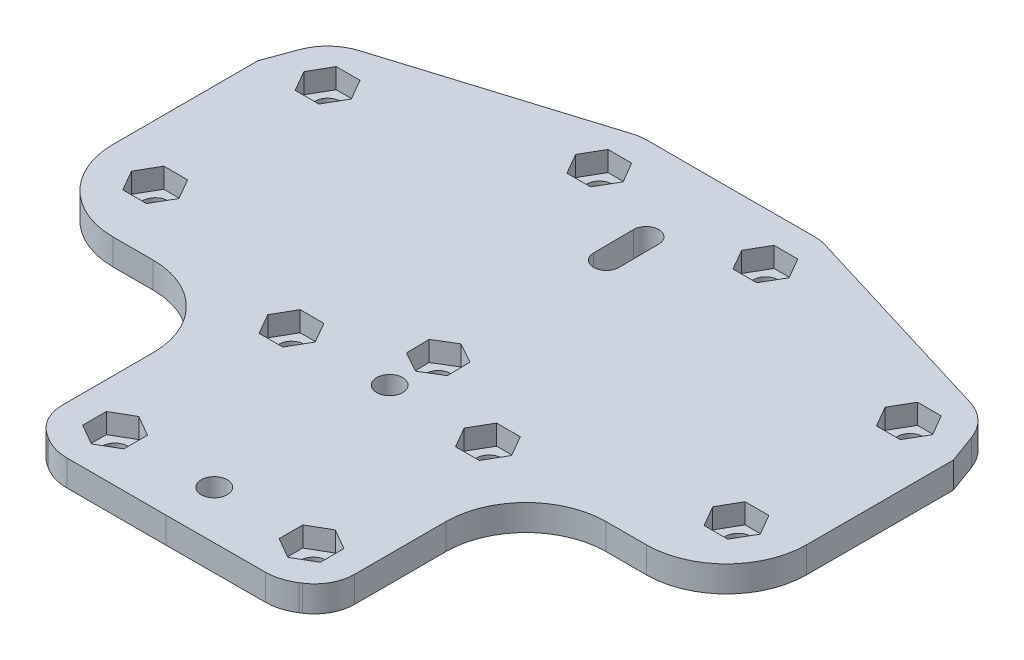
SolidWorks part; units mm, degrees
ref_plane "Front Plane" through (0, 0, 0) normal (0, 0, 1) x (1, 0, 0)
ref_plane "Top Plane" through (0, 0, 0) normal (0, 1, 0) x (1, 0, 0)
ref_plane "Right Plane" through (0, 0, 0) normal (1, 0, 0) x (0, 0, -1)
sketch "DimensionalReference" plane through (0, 0, 0) normal (0, 1, 0) x (1, 0, 0)
  line L0 (0, 0) -> (0, 54.3246) construction
  line L1 (-1000, 12.5) -> (1000, 12.5) construction
  line L2 (-1000, 12.5) -> (-1000, -12.5) construction
  line L3 (-1000, -12.5) -> (1000, -12.5) construction
  line L4 (1000, 12.5) -> (1000, -12.5) construction
  line L5 (-72.5, -22.5) -> (-72.5, 60.05) construction
  line L6 (0, 22.5) -> (0, -109.2175) construction
  line L7 (-12.5, -17.5) -> (12.9, -17.5) construction
  line L8 (-12.5, -17.5) -> (-12.5, -92.5) construction
  line L9 (-12.5, -92.5) -> (12.9, -92.5) construction
  line L10 (12.9, -17.5) -> (12.9, -92.5) construction
  line L11 (-104.4908, -32.4017) -> (-83.7785, 24.5983)
  line L12 (-23.5771, 48.153) -> (-76.0379, 31.9666)
  line L13 (-20.7123, 48.5) -> (20.7123, 48.5)
  line L14 (-93.2123, -36.5) -> (-24.5, -80.5) construction
  line L15 (-24.5, -80.5) -> (24.5, -80.5) construction
  line L16 (93.2123, -36.5) -> (24.5, -80.5) construction
  line L17 (104.4908, -32.4017) -> (83.7785, 24.5983)
  line L18 (23.5771, 48.153) -> (76.0379, 31.9666)
  line L19 (-12.5, -92.5) -> (-24.5, -92.5)
  line L20 (-99.6835, -46.6056) -> (-65.3273, -68.6056)
  line L21 (-65.3273, -68.6056) -> (-30.9712, -90.6056)
  line L22 (0.2, -92.5) -> (-12.5, -92.5)
  line L23 (99.6835, -46.6056) -> (65.3273, -68.6056)
  line L24 (65.3273, -68.6056) -> (30.9712, -90.6056)
  line L25 (12.5, -92.5) -> (24.5, -92.5)
  line L26 (-0.2, -92.5) -> (12.5, -92.5)
  circle A0 centre (0, 22.5) radius 12 construction
  circle A1 centre (-72.5, -22.5) radius 12 construction
  circle A2 centre (72.5, -22.5) radius 12 construction
  circle A3 centre (0, 22.5) radius 15 construction
  circle A4 centre (-72.5, -22.5) radius 15 construction
  circle A5 centre (72.5, -22.5) radius 15 construction
  circle A6 centre (0, 22.5) radius 25
  circle A7 centre (-72.5, -22.5) radius 25
  circle A8 centre (72.5, -22.5) radius 25
  circle A9 centre (-72.5, 20.5) radius 12
  circle A10 centre (-72.5, 20.5) radius 3.25
  circle A11 centre (-93.2123, -36.5) radius 12
  circle A12 centre (-20.7123, 36.5) radius 12
  circle A13 centre (-24.5, -36.5) radius 12
  circle A16 centre (72.5, 20.5) radius 12
  circle A17 centre (93.2123, -36.5) radius 12
  circle A18 centre (24.5, -36.5) radius 12
  circle A19 centre (20.7123, 36.5) radius 12
  circle A20 centre (-24.5, -80.5) radius 12
  circle A21 centre (24.5, -80.5) radius 12
  circle A22 centre (-58.8562, -58.5) radius 12
  circle A23 centre (58.8562, -58.5) radius 12
  point P0 (0, 0)
  point P24 (0, -262.4926)
  point P39 (0, 48.5)
  point P47 (0, -48.5)
  dimension "D3" = 24
  dimension "D10" = 24
  dimension "D11" = 24
  dimension "D13" = 30
  dimension "D14" = 30
  dimension "D15" = 30
  dimension "D16" = 50
  dimension "D17" = 50
  dimension "D18" = 50
  dimension "D19" = 24
  dimension "D21" = 6.5
  dimension "D22" = 24
  dimension "D29" = 24
  dimension "D31" = 12
  dimension "D32" = 12
  dimension "D1" = 2000
  dimension "D2" = 25
  dimension "D4" = 22.5
  dimension "D5" = 12.5
  dimension "D6" = 1000
  dimension "D7" = 145
  dimension "D8" = 72.5
  dimension "D9" = 22.5
  dimension "D12" = 22.5
  dimension "D20" = 8
  dimension "D23" = 24
  dimension "D24" = 24
  dimension "D25" = 25.4
  dimension "D26" = 75
  dimension "D27" = 12.5
  dimension "D28" = 5
  dimension "D30" = 12
sketch "Sketch2" plane through (0, 0, 0) normal (0, 1, 0) x (1, 0, 0)
  line L0 (24.8999, -92.4299) -> (0.2, -92.5)
  line L1 (-104.4908, -32.4017) -> (-83.7785, 24.5983)
  line L2 (-76.0379, 31.9666) -> (-24.9114, 47.7413)
  line L3 (0, 48.5) -> (-20.7123, 48.5)
  line L4 (-99.6835, -46.6056) -> (-30.9712, -90.6056)
  line L5 (0, 48.5) -> (0.2, -92.5) construction
  line L6 (-24.5, -92.5) -> (0.2, -92.5)
  line L7 (99.9529, -46.3225) -> (31.3657, -90.5172)
  line L8 (0, 48.5) -> (20.7122, 48.5588)
  line L9 (76.0845, 32.1824) -> (24.9134, 47.812)
  line L10 (104.7199, -32.1049) -> (83.8459, 24.8361)
  line L11 (-0.044, 27.5) -> (0.044, 17.5) construction
  line L12 (3.1059, 27.5277) -> (3.1938, 17.5277)
  line L13 (-3.1938, 27.4723) -> (-3.1059, 17.4723)
  line L28 (-24.5, -36.5) -> (24.5, -36.5) construction
  line L29 (-24.5, -80.5) -> (24.8659, -80.43) construction
  line L30 (0, 0) -> (139.3739, 0) construction
  arc A0 (-20.7123, 48.5) -> (-24.9114, 47.7413) centre (-20.7123, 36.5) ccw
  arc A6 (-30.9712, -90.6056) -> (-24.5, -92.5) centre (-24.5, -80.5) ccw
  arc A8 (-104.4908, -32.4017) -> (-99.6835, -46.6056) centre (-93.2123, -36.5) ccw
  arc A10 (-76.0379, 31.9666) -> (-83.7785, 24.5983) centre (-72.5, 20.5) ccw
  arc A11 (104.7199, -32.1049) -> (99.9529, -46.3225) centre (93.4531, -36.2352) cw
  arc A12 (76.0845, 32.1824) -> (83.8459, 24.8361) centre (72.5791, 20.7058) cw
  arc A13 (31.3657, -90.5172) -> (24.8999, -92.4299) centre (24.8659, -80.43) cw
  arc A14 (20.7122, 48.5588) -> (24.9134, 47.812) centre (20.7463, 36.5588) cw
  circle A15 centre (-72.5, 20.5) radius 3.15
  circle A16 centre (-20.7123, 36.5) radius 3.15
  circle A17 centre (-93.2123, -36.5) radius 3.15
  circle A18 centre (-58.8562, -58.5) radius 3.15
  circle A19 centre (-24.5, -80.5) radius 3.15
  circle A20 centre (-24.5, -36.5) radius 3.15
  circle A21 centre (-72.5, -22.5) radius 3.15
  arc A23 (3.1059, 27.5277) -> (-3.1938, 27.4723) centre (-0.044, 27.5) ccw
  arc A24 (-3.1059, 17.4723) -> (3.1938, 17.5277) centre (0.044, 17.5) ccw
  circle A25 centre (24.741, -36.4302) radius 3.15
  circle A26 centre (24.8659, -80.43) radius 3.15
  circle A27 centre (59.1595, -58.3326) radius 3.15
  circle A28 centre (93.4531, -36.2352) radius 3.15
  circle A29 centre (72.7011, -22.294) radius 3.15
  circle A30 centre (72.5791, 20.7058) radius 3.15
  circle A31 centre (20.7463, 36.5588) radius 3.15
  circle A32 centre (0, -36.5) radius 3.25
  circle A33 centre (0.1829, -80.465) radius 3.25
  circle A36 centre (0.1035, -24.5) radius 3.1
  point P22 (0, 22.5)
  dimension "D1" = 6.3
  dimension "D2" = 3.15
  dimension "D6" = 6.5
  dimension "D7" = 6.5
  dimension "D4" = 6.2
  dimension "D3" = 10
  dimension "D5" = 12
extrude "MainPlate" add sketch "Sketch2" along normal blind 6.5
sketch "Sketch8" plane through (0, 6.5, 0) normal (0, 1, 0) x (1, 0, 0)
  line L7 (-4.8355, -27.4899) -> (0.2234, -30.2723)
  line L8 (0.2234, -30.2723) -> (5.1624, -27.2824)
  line L9 (-18.5822, -36.5) -> (-21.5411, -31.375)
  line L10 (-21.5411, -31.375) -> (-27.4589, -31.375)
  line L11 (-27.4589, -31.375) -> (-30.4178, -36.5)
  line L12 (-30.4178, -36.5) -> (-27.4589, -41.625)
  line L13 (-27.4589, -41.625) -> (-21.5411, -41.625)
  line L14 (-21.5411, -41.625) -> (-18.5822, -36.5)
  line L15 (-66.5822, -22.5) -> (-69.5411, -17.375)
  line L16 (-69.5411, -17.375) -> (-75.4589, -17.375)
  line L17 (-75.4589, -17.375) -> (-78.4178, -22.5)
  line L18 (-78.4178, -22.5) -> (-75.4589, -27.625)
  line L19 (-75.4589, -27.625) -> (-69.5411, -27.625)
  line L20 (-69.5411, -27.625) -> (-66.5822, -22.5)
  line L21 (-66.5822, 20.5) -> (-69.5411, 25.625)
  line L22 (-69.5411, 25.625) -> (-75.4589, 25.625)
  line L23 (-75.4589, 25.625) -> (-78.4178, 20.5)
  line L24 (-78.4178, 20.5) -> (-75.4589, 15.375)
  line L25 (-75.4589, 15.375) -> (-69.5411, 15.375)
  line L26 (-69.5411, 15.375) -> (-66.5822, 20.5)
  line L27 (-87.2945, -36.5) -> (-90.2534, -31.375)
  line L28 (-90.2534, -31.375) -> (-96.1712, -31.375)
  line L29 (-96.1712, -31.375) -> (-99.1302, -36.5)
  line L30 (-99.1302, -36.5) -> (-96.1712, -41.625)
  line L31 (-96.1712, -41.625) -> (-90.2534, -41.625)
  line L32 (-90.2534, -41.625) -> (-87.2945, -36.5)
  line L33 (-52.9383, -58.5) -> (-55.8972, -53.375)
  line L34 (-55.8972, -53.375) -> (-61.8151, -53.375)
  line L35 (-61.8151, -53.375) -> (-64.774, -58.5)
  line L36 (-64.774, -58.5) -> (-61.8151, -63.625)
  line L37 (-61.8151, -63.625) -> (-55.8972, -63.625)
  line L38 (-55.8972, -63.625) -> (-52.9383, -58.5)
  line L39 (-24.5, -74.5822) -> (-29.625, -77.5411)
  line L40 (-29.625, -77.5411) -> (-29.625, -83.4589)
  line L41 (-29.625, -83.4589) -> (-24.5, -86.4178)
  line L42 (-24.5, -86.4178) -> (-19.375, -83.4589)
  line L43 (-19.375, -83.4589) -> (-19.375, -77.5411)
  line L44 (-19.375, -77.5411) -> (-24.5, -74.5822)
  line L45 (-14.7945, 36.5) -> (-17.7534, 41.625)
  line L46 (-17.7534, 41.625) -> (-23.6712, 41.625)
  line L47 (-23.6712, 41.625) -> (-26.6302, 36.5)
  line L48 (-26.6302, 36.5) -> (-23.6712, 31.375)
  line L49 (-23.6712, 31.375) -> (-17.7534, 31.375)
  line L50 (-17.7534, 31.375) -> (-14.7945, 36.5)
  line L51 (17.7534, 31.375) -> (14.7945, 36.5)
  line L52 (23.6712, 31.375) -> (17.7534, 31.375)
  line L53 (26.6302, 36.5) -> (23.6712, 31.375)
  line L54 (23.6712, 41.625) -> (26.6302, 36.5)
  line L55 (17.7534, 41.625) -> (23.6712, 41.625)
  line L56 (14.7945, 36.5) -> (17.7534, 41.625)
  line L57 (19.375, -77.5411) -> (24.5, -74.5822)
  line L58 (19.375, -83.4589) -> (19.375, -77.5411)
  line L59 (24.5, -86.4178) -> (19.375, -83.4589)
  line L60 (29.625, -83.4589) -> (24.5, -86.4178)
  line L61 (29.625, -77.5411) -> (29.625, -83.4589)
  line L62 (24.5, -74.5822) -> (29.625, -77.5411)
  line L63 (55.8972, -63.625) -> (52.9383, -58.5)
  line L64 (61.8151, -63.625) -> (55.8972, -63.625)
  line L65 (64.774, -58.5) -> (61.8151, -63.625)
  line L66 (61.8151, -53.375) -> (64.774, -58.5)
  line L67 (55.8972, -53.375) -> (61.8151, -53.375)
  line L68 (52.9383, -58.5) -> (55.8972, -53.375)
  line L69 (90.2534, -41.625) -> (87.2945, -36.5)
  line L70 (96.1712, -41.625) -> (90.2534, -41.625)
  line L71 (99.1302, -36.5) -> (96.1712, -41.625)
  line L72 (96.1712, -31.375) -> (99.1302, -36.5)
  line L73 (90.2534, -31.375) -> (96.1712, -31.375)
  line L74 (87.2945, -36.5) -> (90.2534, -31.375)
  line L75 (69.5411, 15.375) -> (66.5822, 20.5)
  line L76 (75.4589, 15.375) -> (69.5411, 15.375)
  line L77 (78.4178, 20.5) -> (75.4589, 15.375)
  line L78 (75.4589, 25.625) -> (78.4178, 20.5)
  line L79 (69.5411, 25.625) -> (75.4589, 25.625)
  line L80 (66.5822, 20.5) -> (69.5411, 25.625)
  line L81 (69.5411, -27.625) -> (66.5822, -22.5)
  line L82 (75.4589, -27.625) -> (69.5411, -27.625)
  line L83 (78.4178, -22.5) -> (75.4589, -27.625)
  line L84 (75.4589, -17.375) -> (78.4178, -22.5)
  line L85 (69.5411, -17.375) -> (75.4589, -17.375)
  line L86 (66.5822, -22.5) -> (69.5411, -17.375)
  line L87 (21.5411, -41.625) -> (18.5822, -36.5)
  line L88 (27.4589, -41.625) -> (21.5411, -41.625)
  line L89 (30.4178, -36.5) -> (27.4589, -41.625)
  line L90 (27.4589, -31.375) -> (30.4178, -36.5)
  line L91 (21.5411, -31.375) -> (27.4589, -31.375)
  line L92 (18.5822, -36.5) -> (21.5411, -31.375)
  line L93 (5.1624, -27.2824) -> (5.0426, -21.5101)
  line L94 (5.0426, -21.5101) -> (-0.0163, -18.7277)
  line L95 (-0.0163, -18.7277) -> (-4.9553, -21.7176)
  line L96 (-4.9553, -21.7176) -> (-4.8355, -27.4899)
  circle A0 centre (0.1035, -24.5) radius 5 construction
  circle A1 centre (-24.5, -36.5) radius 5.125 construction
  circle A2 centre (-72.5, -22.5) radius 5.125 construction
  circle A3 centre (-72.5, 20.5) radius 5.125 construction
  circle A4 centre (-93.2123, -36.5) radius 5.125 construction
  circle A5 centre (-58.8562, -58.5) radius 5.125 construction
  circle A6 centre (-24.5, -80.5) radius 5.125 construction
  circle A7 centre (-20.7123, 36.5) radius 5.125 construction
  circle A8 centre (20.7123, 36.5) radius 5.125 construction
  circle A9 centre (24.5, -80.5) radius 5.125 construction
  circle A10 centre (58.8562, -58.5) radius 5.125 construction
  circle A11 centre (93.2123, -36.5) radius 5.125 construction
  circle A12 centre (72.5, 20.5) radius 5.125 construction
  circle A13 centre (72.5, -22.5) radius 5.125 construction
  circle A14 centre (24.5, -36.5) radius 5.125 construction
  point P2 (2.6929, -28.7773)
  dimension "D1" = 10
  dimension "D2" = 10.25
  dimension "D3" = 10.25
  dimension "D4" = 10.25
  dimension "D5" = 10.25
  dimension "D6" = 10.25
  dimension "D7" = 10.25
  dimension "D8" = 10.25
extrude "PressFitNuts" cut sketch "Sketch8" against normal blind 5
sketch "Sketch9" plane through (0, 6.5, 0) normal (0, 1, 0) x (1, 0, 0)
  line L0 (52.6627, -41.5446) -> (50.906, -42.448)
  line L1 (46.1928, -40.9361) -> (17.801, 14.2744)
  line L2 (20.9136, 19.375) -> (51.1306, 19.375)
  line L3 (54.6306, 15.8706) -> (54.562, -38.4365)
  line L4 (0.2, -92.5) -> (0.1035, -24.5) construction
  line L5 (0, 48.5) -> (-20.7123, 48.5) construction
  line L8 (1.0348, -68.2409) -> (25.7237, -61.874)
  line L9 (25.7235, -55.0957) -> (1.0165, -48.7258)
  line L10 (75.4589, -17.375) -> (69.5411, -17.375) construction
  line L11 (17.7534, 31.375) -> (23.6712, 31.375) construction
  line L12 (104.7199, -32.1049) -> (83.8459, 24.8361) construction
  line L13 (3.1938, 17.5277) -> (3.1059, 27.5277) construction
  line L14 (72.4743, -5.375) -> (70.1082, -5.375)
  line L15 (66.6082, -1.8706) -> (66.6107, 0.0995)
  line L16 (72.3516, 2.7836) -> (74.7152, 0.8136)
  line L21 (73.0837, -41.5737) -> (69.4223, -40.2688)
  line L22 (68.257, -41.7691) -> (72.4275, -47.9662)
  line L23 (74.1008, -47.9448) -> (74.8613, -46.7499)
  line L24 (87.2945, -36.5) -> (90.2534, -41.625) construction
  line L25 (64.774, -58.5) -> (61.8151, -53.375) construction
  line L26 (31.3657, -90.5172) -> (99.9529, -46.3225) construction
  line L27 (-73.8269, -48.1547) -> (-74.5908, -46.9619)
  line L28 (-68.0006, -41.9624) -> (-72.1536, -48.1713)
  line L29 (-72.8278, -41.7807) -> (-69.1702, -40.4654)
  line L31 (-72.2216, 2.5786) -> (-74.5796, 0.6018)
  line L32 (-66.465, -2.0593) -> (-66.4731, -0.0893)
  line L33 (-72.3212, -5.5804) -> (-69.9551, -5.5737)
  line L34 (-25.4295, -55.1682) -> (-0.7407, -48.7283)
  line L35 (-0.7036, -68.2434) -> (-25.4105, -61.9465)
  line L38 (-54.5378, 15.7157) -> (-54.3152, -38.5909)
  line L39 (-20.8309, 19.3158) -> (-51.0478, 19.2301)
  line L40 (-45.9389, -41.0668) -> (-17.7039, 14.224)
  line L41 (-52.407, -41.6937) -> (-50.6478, -42.5921)
  line L42 (0.0562, 8.8531) -> (0, 48.5) construction
  circle A0 centre (0, -36.5) radius 3.25 construction
  circle A1 centre (0.1829, -80.465) radius 3.25 construction
  circle A2 centre (0.1829, -80.465) radius 3.25 construction
  circle A3 centre (0.2411, -36.4997) radius 3.25 construction
  arc A4 (-20.8309, 19.3158) -> (-17.7039, 14.224) centre (-20.821, 15.8158) cw
  arc A5 (-54.5378, 15.7157) -> (-51.0478, 19.2301) centre (-51.0378, 15.7301) cw
  arc A6 (-74.5796, 0.6018) -> (-72.3212, -5.5804) centre (-72.3311, -2.0804) ccw
  arc A7 (-72.2216, 2.5786) -> (-66.4731, -0.0893) centre (-69.9731, -0.1036) cw
  arc A8 (-66.465, -2.0593) -> (-69.9551, -5.5737) centre (-69.965, -2.0737) cw
  arc A9 (-74.5908, -46.9619) -> (-72.8278, -41.7807) centre (-71.6435, -45.0742) cw
  arc A10 (-54.3152, -38.5909) -> (-52.407, -41.6937) centre (-50.8152, -38.5766) ccw
  arc A11 (-45.9389, -41.0668) -> (-50.6478, -42.5921) centre (-49.056, -39.475) cw
  arc A12 (-25.4295, -55.1682) -> (-25.4105, -61.9465) centre (-24.5461, -58.5549) ccw
  arc A13 (25.7237, -61.874) -> (25.7235, -55.0957) centre (24.8497, -58.4849) ccw
  arc A14 (1.0348, -68.2409) -> (-0.7036, -68.2434) centre (0.1608, -64.8518) cw
  arc A15 (1.0165, -48.7258) -> (-0.7407, -48.7283) centre (0.1427, -52.115) ccw
  arc A21 (17.801, 14.2744) -> (20.9136, 19.375) centre (20.9136, 15.875) cw
  arc A22 (51.1306, 19.375) -> (54.6306, 15.8706) centre (51.1306, 15.875) cw
  arc A23 (50.906, -42.448) -> (46.1928, -40.9361) centre (49.3054, -39.3355) cw
  arc A24 (52.6627, -41.5446) -> (54.562, -38.4365) centre (51.062, -38.4321) ccw
  arc A25 (73.0837, -41.5737) -> (74.8613, -46.7499) centre (71.9087, -44.8706) cw
  arc A26 (66.6107, 0.0995) -> (72.3516, 2.7836) centre (70.1107, 0.0951) cw
  arc A27 (70.1082, -5.375) -> (66.6082, -1.8706) centre (70.1082, -1.875) cw
  arc A28 (72.4743, -5.375) -> (74.7152, 0.8136) centre (72.4743, -1.875) ccw
  arc A29 (-73.8269, -48.1547) -> (-72.1536, -48.1713) centre (-72.9848, -47.6153) ccw
  arc A30 (-68.0006, -41.9624) -> (-69.1702, -40.4654) centre (-68.8318, -41.4064) ccw
  arc A31 (72.4275, -47.9662) -> (74.1008, -47.9448) centre (73.2571, -47.4079) ccw
  arc A32 (69.4223, -40.2688) -> (68.257, -41.7691) centre (69.0866, -41.2108) ccw
  point P72 (-15.0954, 19.3321)
  point P75 (-54.5522, 19.2201)
  point P78 (-81.9869, -5.6078)
  point P81 (-66.5037, 7.372)
  point P84 (-66.4507, -5.5637)
  point P87 (-76.9581, -43.2658)
  point P90 (-54.3064, -40.7237)
  point P93 (-47.5307, -44.1838)
  point P96 (-38.5637, -58.5942)
  point P99 (38.8673, -58.4844)
  point P102 (0.1659, -68.465)
  point P105 (0.1376, -48.4992)
  point P108 (0.0559, 9.0631)
  point P111 (-8.3883, 6.0805)
  point P114 (-11.4986, -24.5329)
  point P117 (11.7057, -24.5)
  point P120 (8.5087, 6.1045)
  point P123 (15.1781, 19.375)
  point P126 (54.635, 19.375)
  point P129 (47.7934, -44.0486)
  point P132 (54.5593, -40.5693)
  point P135 (77.2181, -43.0472)
  point P138 (66.6201, 7.5608)
  point P141 (66.6038, -5.375)
  point P144 (82.1401, -5.375)
  point P147 (-73.0029, -49.4411)
  point P150 (-66.3118, -39.4376)
  point P153 (73.2805, -49.2336)
  point P156 (66.561, -39.2491)
  dimension "D25" = 3.5
  dimension "D26" = 1
  dimension "D1" = 12
  dimension "D2" = 12
  dimension "D3" = 12
  dimension "D4" = 12
  dimension "D5" = 12
  dimension "D6" = 12
  dimension "D7" = 12
  dimension "D8" = 12
  dimension "D9" = 8.3423
  dimension "D10" = 12
  dimension "D11" = 12
  dimension "D13" = 12
  dimension "D14" = 12
  dimension "D15" = 12
  dimension "D16" = 12
  dimension "D17" = 12
  dimension "D18" = 12
  dimension "D19" = 12
  dimension "D20" = 12
  dimension "D21" = 12
  dimension "D22" = 12
  dimension "D23" = 12
  dimension "D24" = 12
sketch "Sketch11" plane through (0, 0, 0) normal (0, 1, 0) x (1, 0, 0)
  line L0 (0, -4.5) -> (0, 116.15) construction
  line L1 (-111.9, 4.5) -> (-111.9, -116.15)
  line L2 (-86.5, 4.5) -> (-86.5, -19)
  line L3 (-111.9, -116.15) -> (-86.5, -116.15)
  line L4 (86.5, 4.5) -> (86.5, 44.5764)
  line L5 (-86.5, 4.5) -> (-86.5, 44.5764)
  line L6 (-86.5, 44.5764) -> (-111.9, 44.5764)
  line L7 (-111.9, 4.5) -> (-111.9, 44.5764)
  line L8 (-86.5, -116.15) -> (-36.5, -116.15)
  line L9 (-66.5, -39) -> (-56.5, -39)
  line L10 (-36.5, -116.15) -> (-36.5, -59)
  line L11 (86.5, 44.5764) -> (111.9, 44.5764)
  line L12 (111.9, 4.5) -> (111.9, 44.5764)
  line L13 (111.9, 4.5) -> (111.9, -116.15)
  line L14 (111.9, -116.15) -> (86.5, -116.15)
  line L15 (86.5, -116.15) -> (36.5, -116.15)
  line L16 (36.5, -116.15) -> (36.5, -59)
  line L17 (66.5, -39) -> (56.5, -39)
  line L18 (86.5, 4.5) -> (86.5, -19)
  circle A0 centre (-24.5, -85) radius 3.15 construction
  circle A1 centre (-72.5, -27) radius 3.15 construction
  arc A2 (-56.5, -39) -> (-36.5, -59) centre (-56.5, -59) cw
  arc A3 (-86.5, -19) -> (-66.5, -39) centre (-66.5, -19) ccw
  arc A4 (56.5, -39) -> (36.5, -59) centre (56.5, -59) ccw
  arc A5 (86.5, -19) -> (66.5, -39) centre (66.5, -19) cw
extrude "Cut-Extrude2" cut sketch "Sketch11" along normal up to surface (6.5 mm away) up to face at (20.7123, 6.5, -36.5)
fillet "Fillet2" radius 10 2 edges at (36.5, 3.25, 87.2089) (-36.5, 3.25, 87.0652)
move or copy body "Body-Move/Copy1" [suppressed] bodies to move or copy 106
